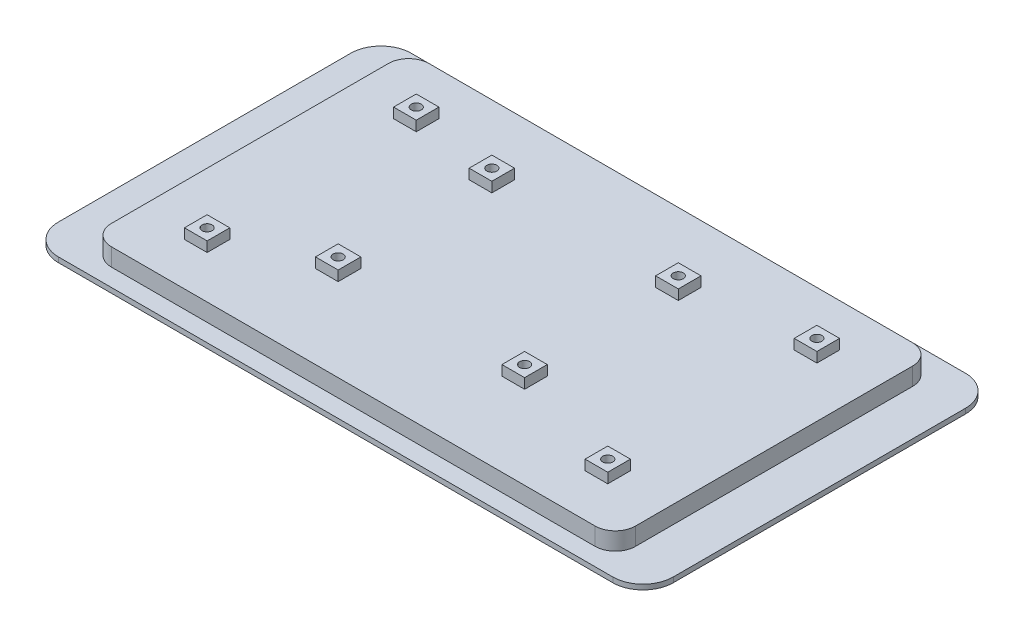
SolidWorks part; units mm, degrees
ref_plane "Front Plane" through (0, 0, 0) normal (0, 0, 1) x (1, 0, 0)
ref_plane "Top Plane" through (0, 0, 0) normal (0, 1, 0) x (1, 0, 0)
ref_plane "Right Plane" through (0, 0, 0) normal (1, 0, 0) x (0, 0, -1)
sketch "Sketch1" plane through (0, 0, 0) normal (0, 1, 0) x (1, 0, 0)
  line L0 (0, 0) -> (0, 41.0945) construction
  line L1 (87.3125, 55.5625) -> (-87.3125, 55.5625)
  line L2 (0, 0) -> (-116.6966, 0) construction
  line L3 (-96.8375, 46.0375) -> (-96.8375, -46.0375)
  line L4 (96.8375, 46.0375) -> (96.8375, -46.0375)
  line L5 (87.3125, -55.5625) -> (-87.3125, -55.5625)
  arc A0 (-87.3125, 55.5625) -> (-96.8375, 46.0375) centre (-87.3125, 46.0375) ccw
  arc A1 (87.3125, 55.5625) -> (96.8375, 46.0375) centre (87.3125, 46.0375) cw
  arc A2 (87.3125, -55.5625) -> (96.8375, -46.0375) centre (87.3125, -46.0375) ccw
  arc A3 (-87.3125, -55.5625) -> (-96.8375, -46.0375) centre (-87.3125, -46.0375) cw
  point P7 (0, -55.5625)
  point P10 (0, 55.5625)
  point P12 (-96.8375, 0)
  point P19 (96.8375, 0)
  dimension "D3" = 9.525
  dimension "D1" = 96.8375
  dimension "D2" = 55.5625
extrude "Boss-Extrude1" add sketch "Sketch1" along normal blind 1.5875
sketch "Sketch2" plane through (0, 1.5875, 0) normal (0, 1, 0) x (1, 0, 0)
  line L0 (0, 0) -> (0, 64.2958) construction
  line L1 (0, 0) -> (-112.017, 0) construction
  line L2 (76.2, 50.0062) -> (-76.2, 50.0062)
  line L3 (-82.55, 43.6562) -> (-82.55, -43.6562)
  line L4 (76.2, -50.0062) -> (-76.2, -50.0062)
  line L5 (82.55, 43.6562) -> (82.55, -43.6562)
  arc A0 (-76.2, 50.0062) -> (-82.55, 43.6562) centre (-76.2, 43.6562) ccw
  arc A1 (-76.2, -50.0062) -> (-82.55, -43.6562) centre (-76.2, -43.6562) cw
  arc A2 (76.2, -50.0062) -> (82.55, -43.6562) centre (76.2, -43.6562) ccw
  arc A3 (76.2, 50.0062) -> (82.55, 43.6562) centre (76.2, 43.6562) cw
  point P8 (0, 50.0062)
  point P13 (-82.55, 0)
  point P19 (82.55, 0)
  point P20 (0, -50.0062)
  dimension "D3" = 6.35
  dimension "D1" = 82.55
  dimension "D2" = 50.0062
extrude "Boss-Extrude2" add sketch "Sketch2" along normal blind 5.5562
sketch "Sketch3" plane through (0, 7.1437, 0) normal (0, 1, 0) x (1, 0, 0)
  line L0 (0, 0) -> (0, -34.5817) construction
  line L1 (-66.675, -29.3687) -> (-59.5312, -29.3687)
  line L2 (-66.675, -29.3687) -> (-66.675, -36.5125)
  line L3 (-66.675, -36.5125) -> (-59.5312, -36.5125)
  line L4 (-59.5312, -29.3687) -> (-59.5312, -36.5125)
  line L9 (0, 0) -> (-71.7488, 0) construction
  line L10 (-66.675, -36.5125) -> (-59.5312, -29.3687) construction
  line L11 (-59.5312, -36.5125) -> (-66.675, -29.3687) construction
  line L12 (59.5312, -29.3687) -> (59.5312, -36.5125)
  line L13 (66.675, -36.5125) -> (59.5312, -36.5125)
  line L14 (66.675, -29.3687) -> (66.675, -36.5125)
  line L15 (66.675, -29.3687) -> (59.5312, -29.3687)
  line L16 (66.675, 29.3687) -> (59.5312, 29.3687)
  line L17 (66.675, 29.3687) -> (66.675, 36.5125)
  line L18 (66.675, 36.5125) -> (59.5312, 36.5125)
  line L19 (59.5312, 29.3687) -> (59.5312, 36.5125)
  line L20 (-59.5312, 36.5125) -> (-66.675, 29.3687) construction
  line L21 (-66.675, 36.5125) -> (-59.5312, 29.3687) construction
  line L22 (-59.5312, 29.3687) -> (-59.5312, 36.5125)
  line L23 (-66.675, 36.5125) -> (-59.5312, 36.5125)
  line L24 (-66.675, 29.3687) -> (-66.675, 36.5125)
  line L25 (-66.675, 29.3687) -> (-59.5312, 29.3687)
  circle A0 centre (-63.1031, -32.9406) radius 1.5875
  circle A1 centre (63.1031, -32.9406) radius 1.5875
  circle A2 centre (63.1031, 32.9406) radius 1.5875
  circle A3 centre (-63.1031, 32.9406) radius 1.5875
  dimension "D5" = 3.175
  dimension "D1" = 66.675
  dimension "D2" = 7.1437
  dimension "D3" = 7.1437
  dimension "D4" = 36.5125
extrude "Boss-Extrude3" add sketch "Sketch3" along normal blind 3.175
sketch "Sketch4" plane through (0, 7.1437, 0) normal (0, 1, 0) x (1, 0, 0)
  line L0 (59.5312, 36.5125) -> (59.5312, 29.3687) construction
  line L1 (76.2, 50.0062) -> (-76.2, 50.0062) construction
  line B0 (20.6362, -23.8125) -> (27.7813, -16.6675) construction
  line B1 (27.7813, -23.8125) -> (20.6362, -23.8125)
  line B2 (27.7813, -23.8125) -> (27.7813, -16.6675)
  line B3 (27.7813, -16.6675) -> (20.6362, -16.6675)
  line B4 (20.6362, -23.8125) -> (20.6362, -16.6675)
  line B5 (20.6362, -16.6675) -> (27.7813, -23.8125) construction
  line B6 (-30.955, -16.6675) -> (-38.1, -23.8125) construction
  line B7 (-30.955, -23.8125) -> (-38.1, -16.6675) construction
  line B8 (-30.955, -23.8125) -> (-30.955, -16.6675)
  line B9 (-38.1, -16.6675) -> (-30.955, -16.6675)
  line B10 (-38.1, -23.8125) -> (-38.1, -16.6675)
  line B11 (-38.1, -23.8125) -> (-30.955, -23.8125)
  line B12 (-30.955, 31.75) -> (-38.1, 24.605) construction
  line B13 (-30.955, 24.605) -> (-38.1, 31.75) construction
  line B14 (20.6362, 24.605) -> (27.7812, 31.75) construction
  line B15 (20.6362, 31.75) -> (27.7813, 24.605) construction
  line B16 (-38.1, 31.75) -> (-30.955, 31.75)
  line B17 (-38.1, 31.75) -> (-38.1, 24.605)
  line B18 (-38.1, 24.605) -> (-30.955, 24.605)
  line B19 (-30.955, 31.75) -> (-30.955, 24.605)
  line B20 (20.6362, 31.75) -> (20.6362, 24.605)
  line B21 (27.7813, 24.605) -> (20.6362, 24.605)
  line B22 (27.7812, 31.75) -> (27.7813, 24.605)
  line B23 (27.7812, 31.75) -> (20.6362, 31.75)
  circle B24 centre (24.2087, -20.24) radius 1.5875
  circle B25 centre (-34.5275, -20.24) radius 1.5875
  circle B26 centre (-34.5275, 28.1775) radius 1.5875
  circle B27 centre (24.2087, 28.1775) radius 1.5875
  dimension "D1" = 31.75
  dimension "D2" = 18.2562
sketch_block_instance "Block1-1"
sketch_block "Block1" parameters "D3"=3.175, "D1"=7.145, "D2"=7.145, "D4"=65.8813, "D5"=55.5625
extrude "Boss-Extrude4" add sketch "Sketch4" along normal blind 3.175
sketch "Sketch5" [suppressed] plane through (0, 0, 0) normal (0, -1, 0) x (1, 0, 0)
  line L4 (-87.3125, -55.5625) -> (87.3125, -55.5625)
  line L5 (96.8375, -46.0375) -> (96.8375, 46.0375)
  line L6 (87.3125, 55.5625) -> (-87.3125, 55.5625)
  line L7 (-96.8375, 46.0375) -> (-96.8375, -46.0375)
  line L8 (-87.3125, -55.5625) -> (87.3125, -55.5625)
  line L9 (96.8375, -46.0375) -> (96.8375, 46.0375)
  line L10 (87.3125, 55.5625) -> (-87.3125, 55.5625)
  line L11 (-96.8375, 46.0375) -> (-96.8375, -46.0375)
  arc A4 (-96.8375, -46.0375) -> (-87.3125, -55.5625) centre (-87.3125, -46.0375) ccw
  arc A5 (87.3125, -55.5625) -> (96.8375, -46.0375) centre (87.3125, -46.0375) ccw
  arc A6 (96.8375, 46.0375) -> (87.3125, 55.5625) centre (87.3125, 46.0375) ccw
  arc A7 (-87.3125, 55.5625) -> (-96.8375, 46.0375) centre (-87.3125, 46.0375) ccw
  arc A8 (-96.8375, -46.0375) -> (-87.3125, -55.5625) centre (-87.3125, -46.0375) ccw
  arc A9 (87.3125, -55.5625) -> (96.8375, -46.0375) centre (87.3125, -46.0375) ccw
  arc A10 (96.8375, 46.0375) -> (87.3125, 55.5625) centre (87.3125, 46.0375) ccw
  arc A11 (-87.3125, 55.5625) -> (-96.8375, 46.0375) centre (-87.3125, 46.0375) ccw
  dimension "D1" = 0
